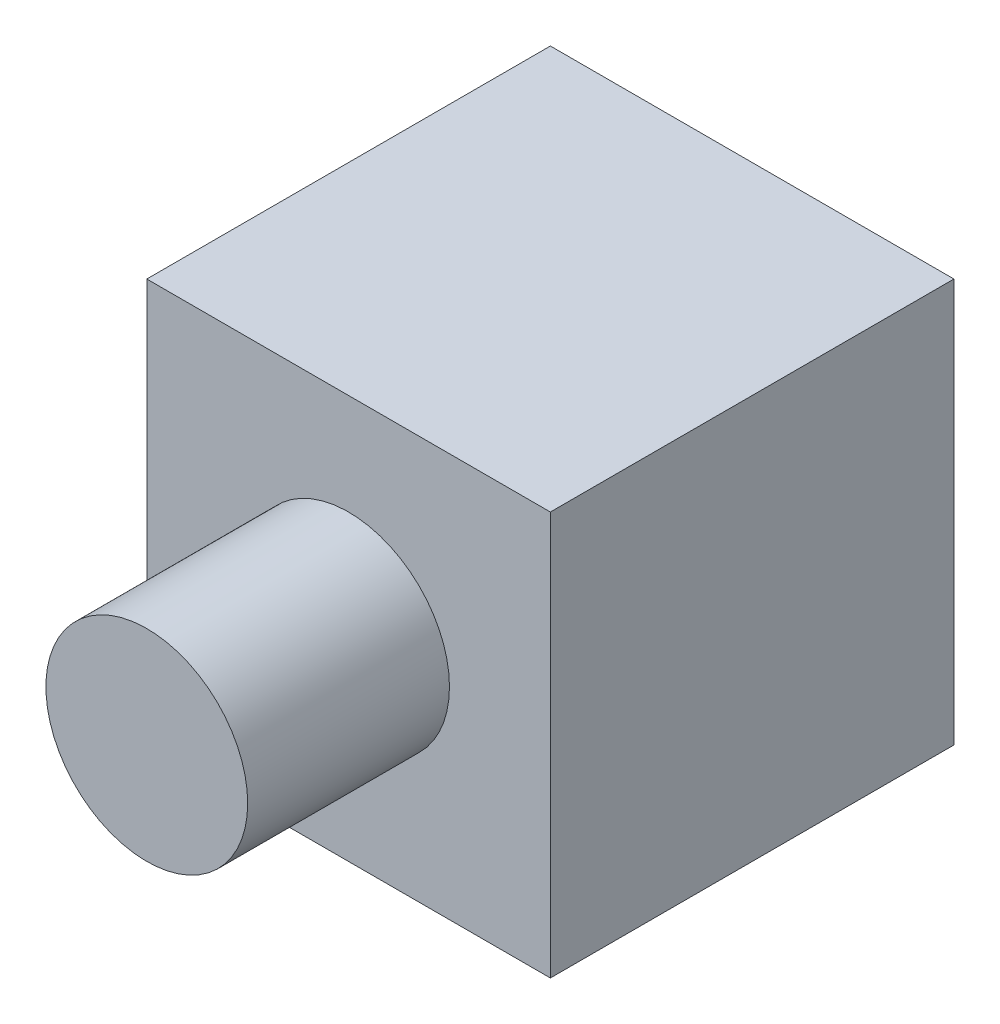
SolidWorks part; units mm, degrees
material "1060 Alloy"
ref_plane "Front Plane" through (0, 0, 0) normal (0, 0, 1) x (1, 0, 0)
ref_plane "Top Plane" through (0, 0, 0) normal (0, 1, 0) x (1, 0, 0)
ref_plane "Right Plane" through (0, 0, 0) normal (1, 0, 0) x (0, 0, -1)
sketch "Sketch1" plane through (0, 0, 0) normal (0, 0, 1) x (1, 0, 0)
  line L1 (-25.4, 25.4) -> (25.4, 25.4)
  line L2 (-25.4, 25.4) -> (-25.4, -25.4)
  line L3 (-25.4, -25.4) -> (25.4, -25.4)
  line L4 (25.4, 25.4) -> (25.4, -25.4)
  line L5 (-25.4, 25.4) -> (25.4, -25.4) construction
  line L6 (-25.4, -25.4) -> (25.4, 25.4) construction
  point P0 (0, 0)
  dimension "D1" = 50.8
extrude "Boss-Extrude1" add sketch "Sketch1" against normal blind 50.8
sketch "Sketch2" plane through (0, 0, 0) normal (0, 0, 1) x (1, 0, 0)
  circle A0 centre (0, 0) radius 12.7
  dimension "D1" = 25.4
extrude "Boss-Extrude2" add sketch "Sketch2" along normal blind 25.4
sketch "Sketch3" plane through (0, 0, -50.8) normal (0, 0, -1) x (-1, 0, 0)
  circle A0 centre (0, 0) radius 12.7
  dimension "D1" = 25.4
extrude "Cut-Extrude1" cut sketch "Sketch3" against normal blind 25.4 contours A0
